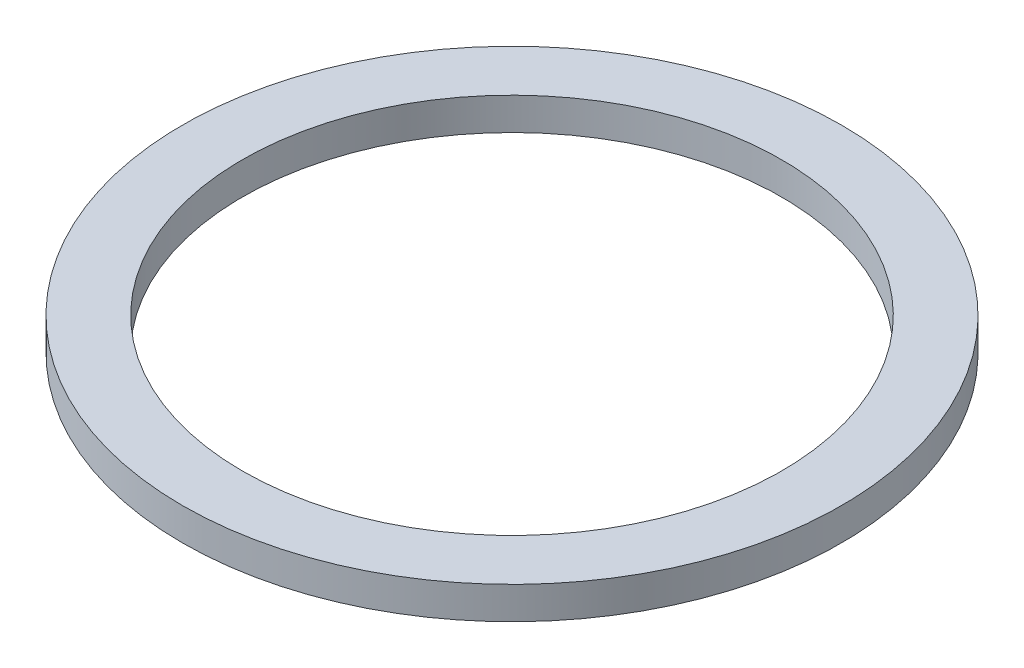
SolidWorks part; units mm, degrees
material "BUTYL"
ref_plane "Front Plane" through (0, 0, 0) normal (0, 0, 1) x (1, 0, 0)
ref_plane "Top Plane" through (0, 0, 0) normal (0, 1, 0) x (1, 0, 0)
ref_plane "Right Plane" through (0, 0, 0) normal (1, 0, 0) x (0, 0, -1)
sketch "Sketch1" plane through (0, 0, 0) normal (0, 1, 0) x (1, 0, 0)
  circle A0 centre (0, 0) radius 16.5
extrude "Boss-Extrude1" add sketch "Sketch1" along normal blind 1.62
sketch "Sketch2" plane through (0, 1.62, 0) normal (0, 1, 0) x (1, 0, 0)
  circle A0 centre (0, 0) radius 13.5
extrude "Cut-Extrude1" cut sketch "Sketch2" against normal blind 1.62
